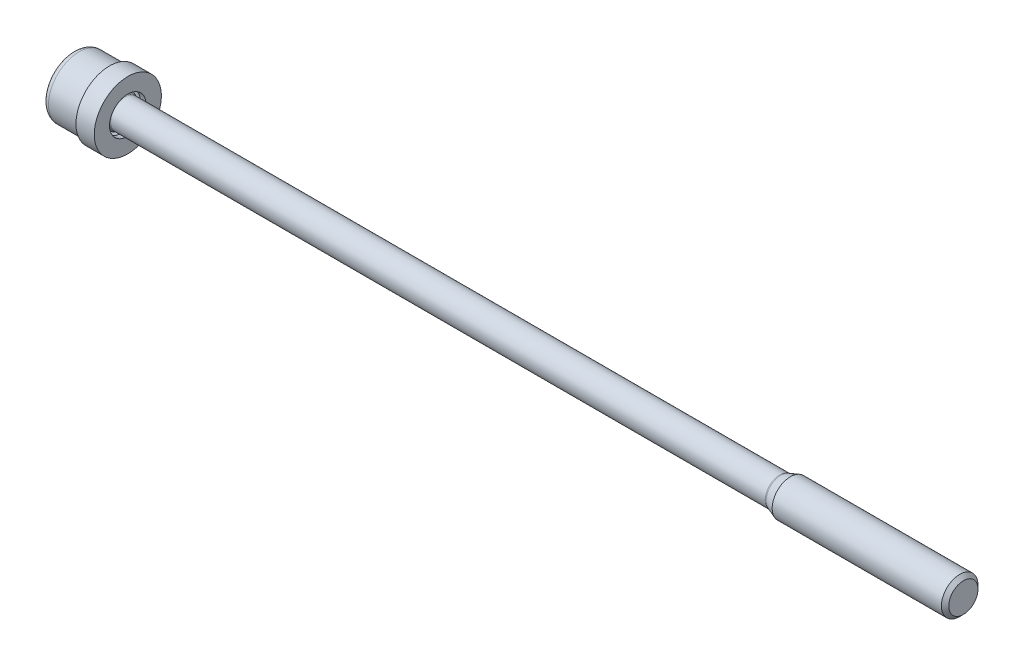
SolidWorks part; units mm, degrees
material "Ti-6Al-2Sn-2Zr-2Mo-2Cr-0.25Si (SS)"
ref_plane "Ebene XY" through (0, 0, 0) normal (0, 0, 1) x (1, 0, 0)
ref_plane "Ebene XZ" through (0, 0, 0) normal (0, 1, 0) x (1, 0, 0)
ref_plane "Ebene YZ" through (0, 0, 0) normal (1, 0, 0) x (0, 0, -1)
sketch "Skizze1" plane through (0, 0, 0) normal (0, 0, 1) x (1, 0, 0)
  line L0 (0, 0) -> (-40.2429, 0) construction
  line L1 (55, 0) -> (-55, 0) construction
  line L2 (0, 5) -> (6, 5)
  line L3 (0, -55) -> (0, 55) construction
  line L4 (6, 5) -> (6, 3.3099)
  line L5 (6, 3.3099) -> (8.5, 2.4)
  line L6 (8.5, 2.4) -> (116, 2.4)
  line L7 (116, 2.4) -> (117.6485, 3)
  line L8 (117.6485, 3) -> (145.4, 3)
  line L9 (145.4, 3) -> (146, 2.4)
  line L10 (146, 2.4) -> (146, 0)
  line L11 (146, 0) -> (4.7321, 0)
  line L12 (4.7321, 0) -> (3, 3)
  line L13 (3, 3) -> (0, 3)
  line L14 (0, 3) -> (0, 5)
  dimension "D1" = 2.5
  dimension "D2" = 20
  dimension "D3" = 140
  dimension "D4" = 20
  dimension "D5" = 4.8
  dimension "D6" = 6
  dimension "D7" = 110
  dimension "D8" = 45
  dimension "D9" = 6
  dimension "D10" = 10
  dimension "D11" = 6
  dimension "D12" = 60
  dimension "D13" = 3
revolve "Rotation1" add sketch "Skizze1" angle 360 about L0
cosmetic thread "Gewindedarstellung1" parameters "D2"=4.891
sketch "Skizze2" plane through (0, 0, 0) normal (-1, 0, 0) x (0, 0, 1)
  line L1 (-2.8868, 0) -> (-1.4434, -2.5)
  line L2 (-1.4434, -2.5) -> (1.4434, -2.5)
  line L3 (1.4434, -2.5) -> (2.8868, 0)
  line L4 (2.8868, 0) -> (1.4434, 2.5)
  line L5 (1.4434, 2.5) -> (-1.4434, 2.5)
  line L6 (-1.4434, 2.5) -> (-2.8868, 0)
  circle A0 centre (0, 0) radius 2.5 construction
  circle A1 centre (0, 0) radius 3 construction
  circle A2 centre (0, 0) radius 3
  dimension "D1" = 5
extrude "Aufsatz-Linear austragen1" add sketch "Skizze2" against normal up to surface (3 mm away)
fillet "Verrundung1" radius 1 1 edges at (0, 0, -5)
fillet "Verrundung2" radius 0.5 3 edges at (116, 0, -2.4) (8.5, 0, -2.4) (6, 0, -3.3099)
sketch "Skizze3" plane through (0, 0, 0) normal (0, 0, 1) x (1, 0, 0)
  line L0 (6, 5.5) -> (9, 5.5)
  line L1 (9, 5.5) -> (9, 3)
  line L2 (9, 3) -> (8.0606, 3)
  line L3 (6, -5) -> (6, 5) construction
  line L4 (6, 3.75) -> (6, 5.5)
  line L5 (8.0606, 3) -> (6, 3.75)
  line L6 (0, 0) -> (9.2776, 0) construction
  line L7 (5.5, 0) -> (-5.5, 0) construction
  dimension "D1" = 6
  dimension "D2" = 7.5
  dimension "D3" = 20
  dimension "D4" = 3
  dimension "D5" = 11
revolve "Rotation2" add sketch "Skizze3" angle 360 about L6
move or copy body "Körper-Verschieben/Kopieren1" [suppressed] bodies to move or copy 103 copy no translate (0, 0, -16)
